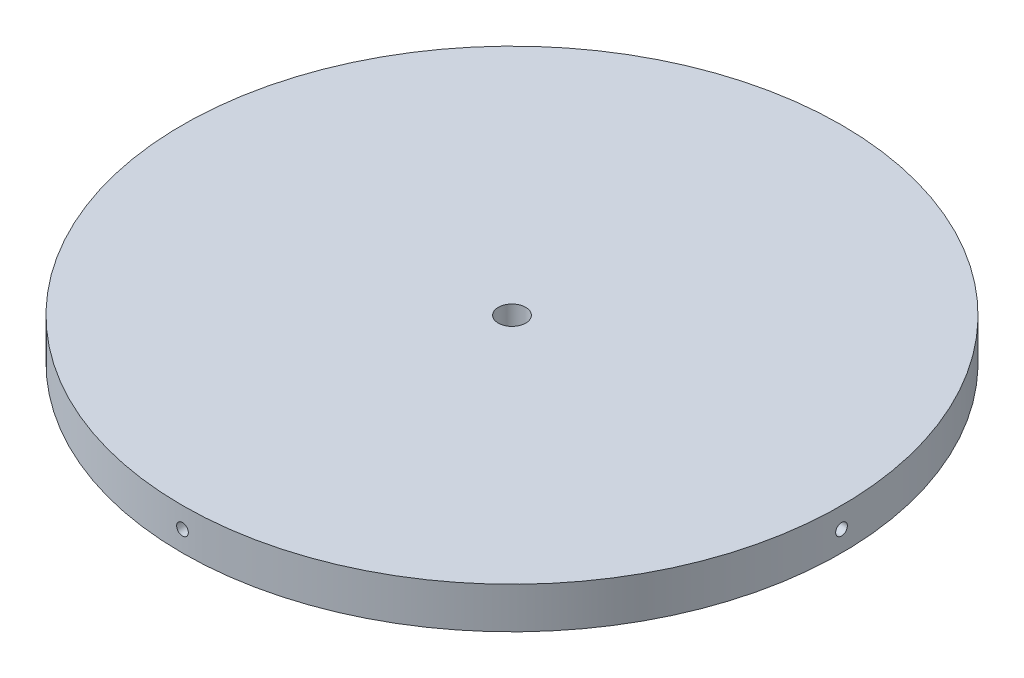
SolidWorks part; units mm, degrees
material "6061-T6 (SS)"
ref_plane "Front Plane" through (0, 0, 0) normal (0, 0, 1) x (1, 0, 0)
ref_plane "Top Plane" through (0, 0, 0) normal (0, 1, 0) x (1, 0, 0)
ref_plane "Right Plane" through (0, 0, 0) normal (1, 0, 0) x (0, 0, -1)
sketch "Sketch1" plane through (0, 0, 0) normal (0, 1, 0) x (1, 0, 0)
  circle A0 centre (0, 0) radius 76.1746
  dimension "D1" = 152.3492
extrude "Boss-Extrude1" add sketch "Sketch1" along normal blind 9.525
sketch "Sketch2" plane through (0, 9.525, 0) normal (0, 1, 0) x (1, 0, 0)
  circle A0 centre (0, 0) radius 3.175
  dimension "D1" = 6.35
extrude "Cut-Extrude1" cut sketch "Sketch2" against normal through all
ref_plane "Plane1" through (0, 0, 76.1746) normal (0, 0, 1) x (1, 0, 0)
hole_wizard "Tap Drill for #6-32 Tap1" positions "Sketch4" profile "Sketch5" hole size "#6-32" standard "ANSI Inch"
sketch "Sketch4" plane through (0, 0, 76.1746) normal (0, 0, 1) x (1, 0, 0)
  line L0 (0, -3.4925) -> (0, 3.4925) construction
  line L1 (83.7921, 0) -> (-83.7921, 0) construction
  point P0 (0, 4.7625)
  dimension "D1" = 4.7625
sketch "Sketch5" plane through (0, 4.7625, 76.1746) normal (1, 0, 0) x (0, -1, 0)
  line L0 (0, 0) -> (0, 10.4647)
  line L1 (0, 10.4647) -> (1.3525, 9.652)
  line L2 (1.3525, 9.652) -> (1.3525, 0)
  line L5 (1.3525, 0) -> (0, 0)
  line L10 (0, 10.4647) -> (-1.3525, 9.652) construction
  line L11 (0, -6.35) -> (0, 107.95) construction
  dimension "Hole Dia." = 2.7051
  dimension "Hole Depth" = 9.652
  dimension "Drill Angle" = 118
pattern_circular "CirPattern1" count 4 every 90 about axis through (0, 9.525, 0) along (0, 1, 0) of "Tap Drill for #6-32 Tap1"
sketch "Sketch6" plane through (0, 9.525, 0) normal (0, 1, 0) x (1, 0, 0)
  circle A0 centre (0, 0) radius 9.525
  dimension "D1" = 19.05
split line "Split Line1" [suppressed]
sketch "Sketch8" [suppressed] plane through (0, 9.525, 0) normal (0, 1, 0) x (1, 0, 0)
  line L0 (-69.7631, 69.7631) -> (75.0995, -75.0995) construction
  line L1 (12.7, -6.35) -> (107.8587, -6.35)
  line L2 (-88.9476, 0) -> (103.0007, 0) construction
  line L3 (107.8587, -6.35) -> (107.8587, -104.2046)
  line L4 (6.35, -12.7) -> (6.35, -108.4135)
  line L5 (6.35, -108.4135) -> (107.8587, -108.4135)
  line L6 (107.8587, -108.4135) -> (107.8587, -104.2046)
  arc A1 (12.7, -6.35) -> (6.35, -12.7) centre (12.7, -12.7) ccw
  dimension "D3" = 6.35
  dimension "D1" = 45
  dimension "D2" = 12.7
extrude "Cut-Extrude2" [suppressed] cut sketch "Sketch8" against normal blind 7.1437
pattern_circular "CirPattern2" [suppressed] count 4 every 90
fillet "Fillet1" [suppressed] radius 1.27
equation "\"Scale\"= 1"
equation "\"CouplerOuterDiameter\"= 5.998in"
equation "\"CouplerInnerDiameter\"= 5.820in"
equation "\"TotalThickness\"= .375in"
equation "\"lipDepth\"= .125in"
equation "\"ScrewDepthEdge\"= .375in"
equation "\"EyeNutDiameter\"= 1 / 4in"
equation "\"WasherDiameter\"= .75"
equation "\"LeadScrewDiameter\"= 3 / 8in"
equation "\"AvionicsBayLeadScrewDist\"= 2in"
equation "\"SlotWidth\"= 1 / 4in"
equation "\"SlotDepth\"=0.125"
equation "\"SlotLength\"= 1in"
equation "\"SlotOffset\"= 1in"
equation "\"BlackPowderHoleDiameter\"= .125in"
equation "\"WireHoleDiameter\"= .107in"
equation "\"BlackPowderHoleDist\"= 3in"
equation "\"WireHoleDist\"= 3.5in"
equation "\"FilletRadius\"= .05in"
equation "\"D1@Boss-Extrude1\"=\"TotalThickness\""
equation "\"D1@Sketch4\"=\"TotalThickness\"/2"
equation "\"D1@Sketch1\"=\"CouplerOuterDiameter\"/\"Scale\""
equation "\"D1@Sketch6\"=\"WasherDiameter\""
equation "\"CutOutOffset\"= .5in"
equation "\"EndMillDiameter\"= .25in"
equation "\"D3@Sketch8\"=\"EndMillDiameter\""
equation "\"CutOutDepth\"= 3 * \"TotalThickness\" / 4"
equation "\"D1@Cut-Extrude2\"=\"CutOutDepth\""
equation "\"D2@Sketch8\"=\"CutOutOffset\""
equation "\"D1@Fillet1\"=\"FilletRadius\""
